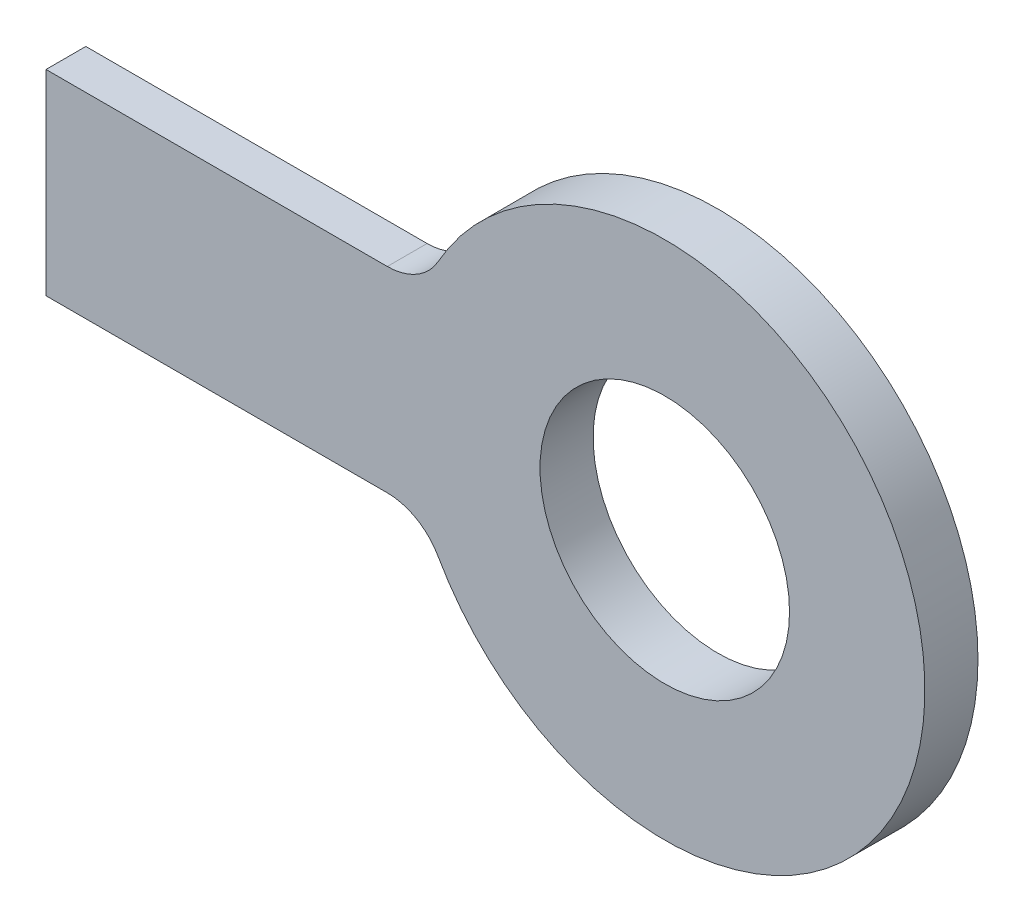
SolidWorks part; units mm, degrees
ref_plane "前视基准面" through (0, 0, 0) normal (0, 0, 1) x (1, 0, 0)
ref_plane "上视基准面" through (0, 0, 0) normal (0, 1, 0) x (1, 0, 0)
ref_plane "右视基准面" through (0, 0, 0) normal (1, 0, 0) x (0, 0, -1)
other "Configuration Table"
sketch "草图1" plane through (0, 0, 0) normal (0, 0, 1) x (1, 0, 0)
  circle A1 centre (-11.8874, -2.7948) radius 98
  circle A2 centre (-11.8874, -2.7948) radius 47
  point P8 (0, 0)
  point P9 (-56.5616, 81.3922)
  point P10 (-51.1404, 87.0005)
  point P11 (-217.819, 33.2915)
extrude "凸台-拉伸1" add sketch "草图1" along normal blind 20
sketch "草图2" plane through (0, 0, 20) normal (0, 0, 1) x (1, 0, 0)
  line L1 (-102.6656, 34.1282) -> (-244.995, 34.1282)
  line L2 (-102.6656, 34.1282) -> (-102.6656, -39.7178)
  line L3 (-102.6656, -39.7178) -> (-244.995, -39.7178)
  line L4 (-244.995, 34.1282) -> (-244.995, -39.7178)
  circle A0 centre (-11.8874, -2.7948) radius 98 construction
  point P6 (-103.1748, -38.4402)
  point P7 (-244.995, 34.1282)
extrude "凸台-拉伸2" add sketch "草图2" against normal blind 15
fillet "圆角1" radius 22 2 edges at (-102.6656, 34.1282, 12.5) (-102.6656, -39.7178, 12.5)
